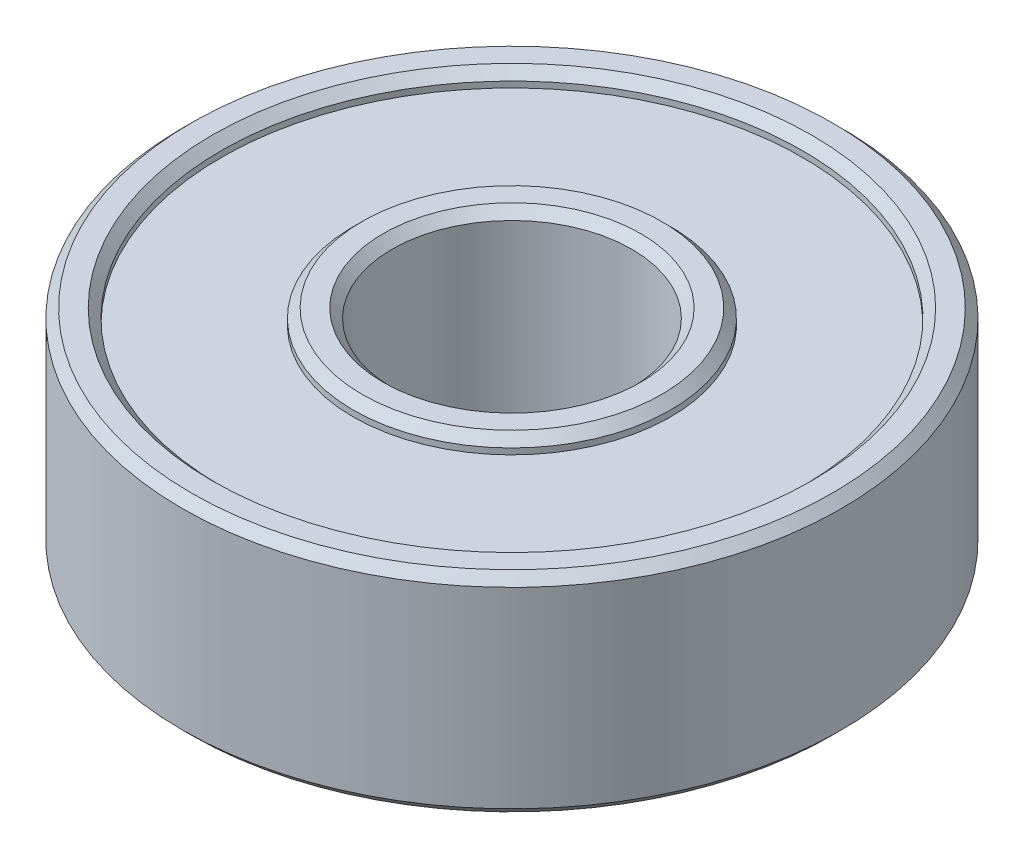
SolidWorks part; units mm, degrees
material "Stainless Steel (ferritic)"
ref_plane "Front Plane" through (0, 0, 0) normal (0, 0, 1) x (1, 0, 0)
ref_plane "Top Plane" through (0, 0, 0) normal (0, 1, 0) x (1, 0, 0)
ref_plane "Right Plane" through (0, 0, 0) normal (1, 0, 0) x (0, 0, -1)
ref_plane "Plane1" through (0, 0, 0) normal (0, 0, -1) x (-1, 0, 0)
sketch "Sketch1" plane through (0, 0, 0) normal (0, 0, -1) x (-1, 0, 0)
  line L0 (-4, 3.2) -> (-4.3, 3.5)
  line L1 (-4.3, 3.5) -> (-5, 3.5)
  line L2 (-5, 3.5) -> (-5.3, 3.2)
  line L3 (-5.3, 3.2) -> (-5.3, 3)
  line L4 (-5.3, 3) -> (-9.7, 3)
  line L5 (-9.7, 3) -> (-9.7, 3.2)
  line L6 (-9.7, 3.2) -> (-10, 3.5)
  line L7 (-10, 3.5) -> (-10.7, 3.5)
  line L8 (-10.7, 3.5) -> (-11, 3.2)
  line L9 (-11, 3.2) -> (-11, -3.2)
  line L10 (-11, -3.2) -> (-10.7, -3.5)
  line L11 (-10.7, -3.5) -> (-10, -3.5)
  line L12 (-10, -3.5) -> (-9.7, -3.2)
  line L13 (-9.7, -3.2) -> (-9.7, -3)
  line L14 (-9.7, -3) -> (-5.3, -3)
  line L15 (-5.3, -3) -> (-5.3, -3.2)
  line L16 (-5.3, -3.2) -> (-5, -3.5)
  line L17 (-5, -3.5) -> (-4.3, -3.5)
  line L18 (-4.3, -3.5) -> (-4, -3.2)
  line L19 (-4, -3.2) -> (-4, 3.2)
  line L20 (0, -3.5) -> (0, 3.5) construction
revolve "Revolve1" add sketch "Sketch1" angle 360 about L20
